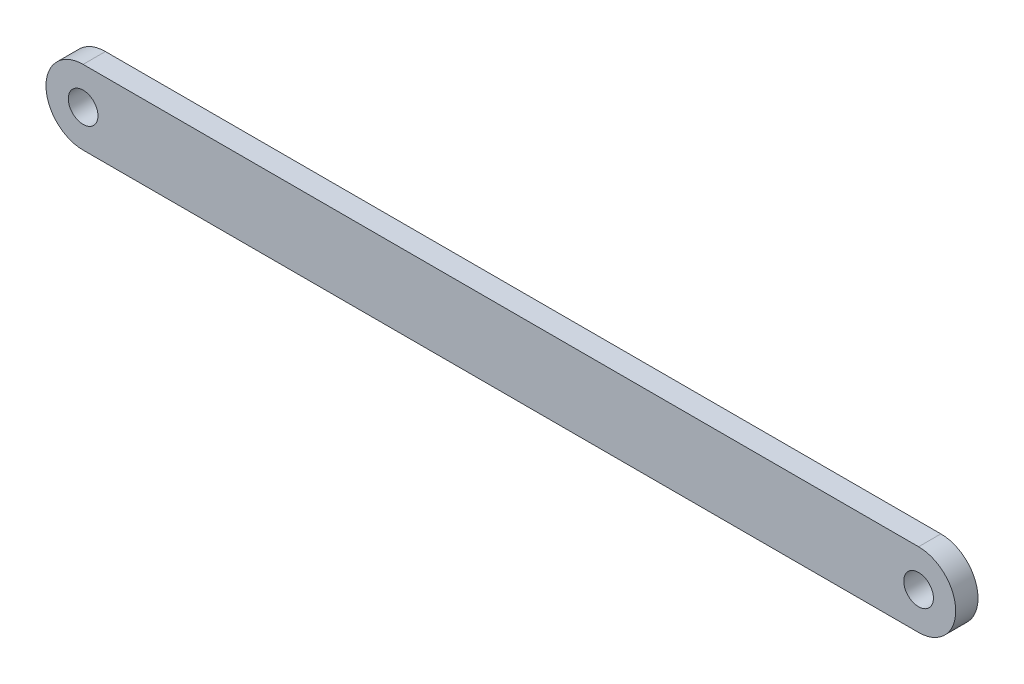
SolidWorks part; units mm, degrees
ref_plane "前视基准面" through (0, 0, 0) normal (0, 0, 1) x (1, 0, 0)
ref_plane "上视基准面" through (0, 0, 0) normal (0, 1, 0) x (1, 0, 0)
ref_plane "右视基准面" through (0, 0, 0) normal (1, 0, 0) x (0, 0, -1)
sketch "草图1" plane through (0, 0, 0) normal (0, 0, 1) x (1, 0, 0)
  line L0 (0, 0) -> (112.5, 0) construction
  line L1 (55, 0) -> (-55, 0) construction
  line L2 (0, 5) -> (112.5, 5)
  line L3 (0, -5) -> (112.5, -5)
  arc A0 (0, 5) -> (0, -5) centre (0, 0) ccw
  arc A1 (112.5, -5) -> (112.5, 5) centre (112.5, 0) ccw
  circle A2 centre (0, 0) radius 2
  circle A3 centre (112.5, 0) radius 2
  point P5 (56.25, 0)
extrude "凸台-拉伸1" add sketch "草图1" along normal mid plane 3
